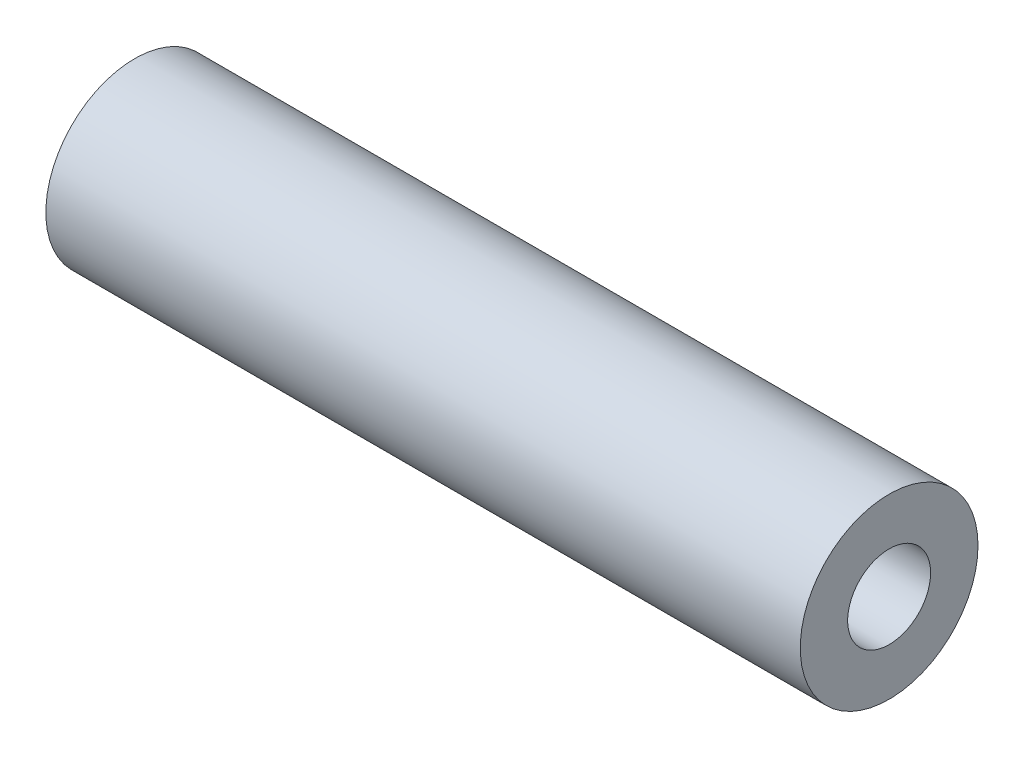
SolidWorks part; units mm, degrees
material "6061-T6 (SS)"
ref_plane "前视基准面" through (0, 0, 0) normal (0, 0, 1) x (1, 0, 0)
ref_plane "上视基准面" through (0, 0, 0) normal (0, 1, 0) x (1, 0, 0)
ref_plane "右视基准面" through (0, 0, 0) normal (1, 0, 0) x (0, 0, -1)
other "Configuration Table"
sketch "草图1" plane through (0, 0, 0) normal (1, 0, 0) x (0, 0, -1)
  circle A0 centre (0, 0) radius 2.1
  circle A1 centre (0, 0) radius 4.5
  dimension "D1" = 4.2
  dimension "D2" = 9
extrude "凸台-拉伸1" add sketch "草图1" along normal blind 38.2
